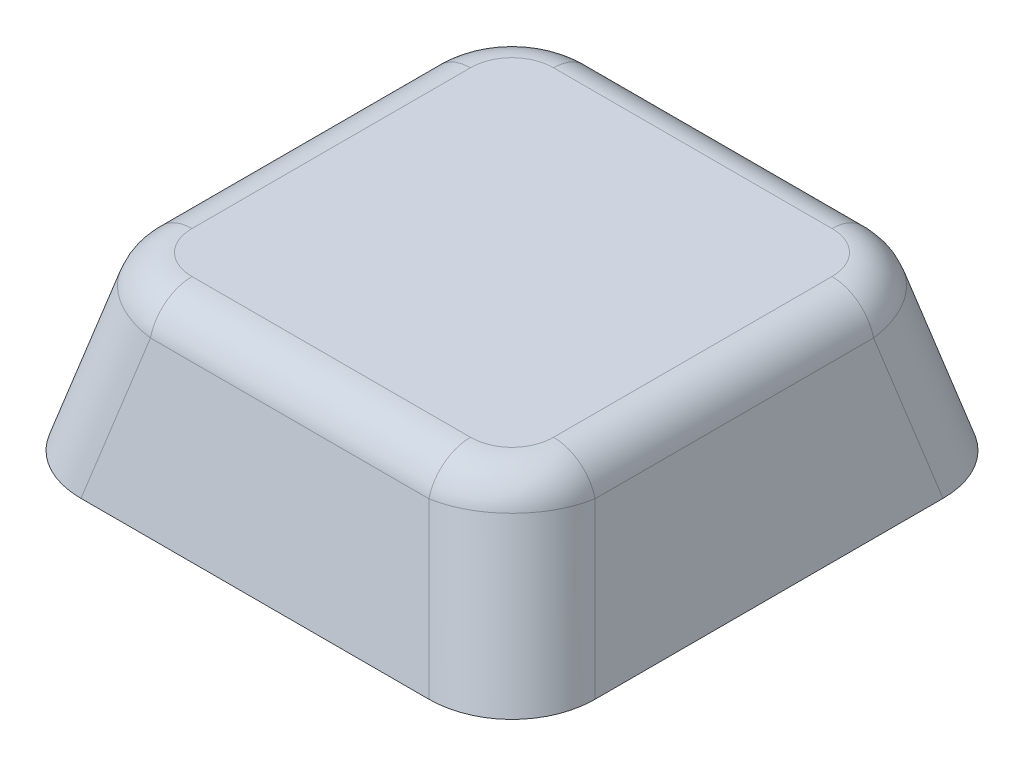
SolidWorks part; units mm, degrees
ref_plane "Front" through (0, 0, 0) normal (0, 0, 1) x (1, 0, 0)
ref_plane "Top" through (0, 0, 0) normal (0, 1, 0) x (1, 0, 0)
ref_plane "Right" through (0, 0, 0) normal (1, 0, 0) x (0, 0, -1)
sketch "草图1" plane through (0, 0, 0) normal (0, 1, 0) x (1, 0, 0)
  line L1 (-3, 3) -> (3, 3)
  line L2 (-3, 3) -> (-3, -3)
  line L3 (-3, -3) -> (3, -3)
  line L4 (3, 3) -> (3, -3)
  line L5 (-3, 3) -> (3, -3) construction
  line L6 (-3, -3) -> (3, 3) construction
  point P0 (0, 0)
  dimension "D1" = 6
  dimension "D2" = 6
ref_plane "基准面1" through (0, 2, 0) normal (0, 1, 0) x (1, 0, 0)
sketch "草图2" plane through (0, 2, 0) normal (0, 1, 0) x (1, 0, 0)
  line L1 (-2.5, 2.5) -> (2.5, 2.5)
  line L2 (-2.5, 2.5) -> (-2.5, -2.5)
  line L3 (-2.5, -2.5) -> (2.5, -2.5)
  line L4 (2.5, 2.5) -> (2.5, -2.5)
  line L5 (-2.5, 2.5) -> (2.5, -2.5) construction
  line L6 (-2.5, -2.5) -> (2.5, 2.5) construction
  point P0 (0, 0)
  dimension "D1" = 5
  dimension "D2" = 5
loft "放样1" add profiles "草图1", "草图2"
fillet "圆角1" radius 1 1 edges
fillet "圆角2" radius 1 1 edges
fillet "圆角3" radius 1 1 edges
fillet "圆角4" radius 1 1 edges
fillet "圆角5" radius 0.5 8 edges
